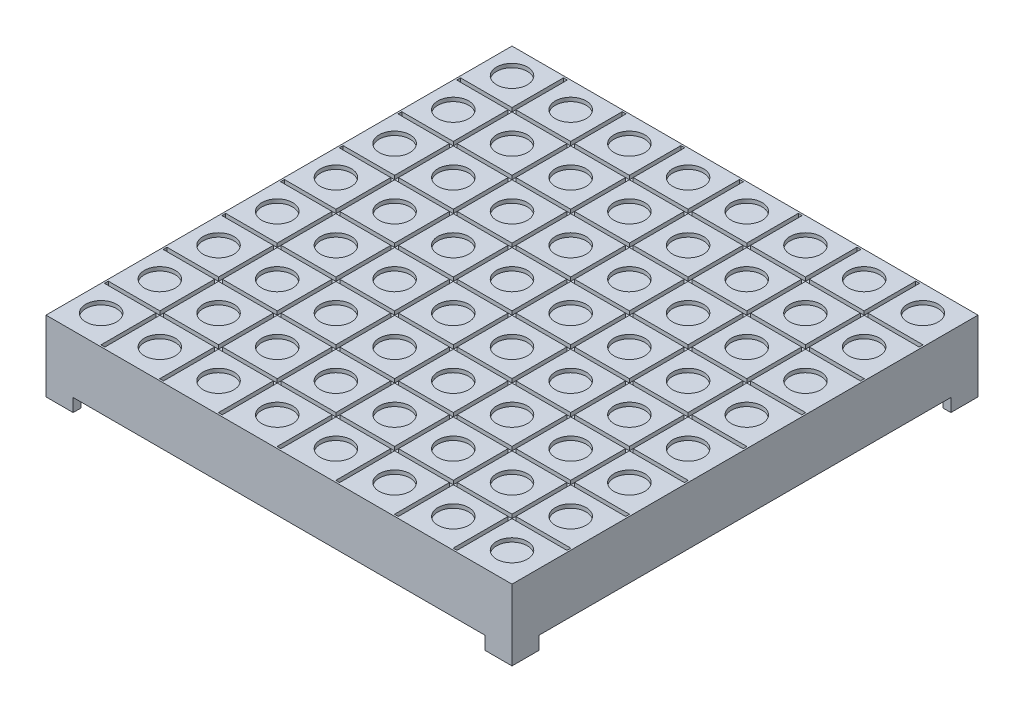
SolidWorks part; units mm, degrees
ref_plane "Спереди" through (0, 0, 0) normal (0, 0, 1) x (1, 0, 0)
ref_plane "Сверху" through (0, 0, 0) normal (0, 1, 0) x (1, 0, 0)
ref_plane "Справа" through (0, 0, 0) normal (1, 0, 0) x (0, 0, -1)
sketch "Эскиз2" plane through (0, 0, 0) normal (0, 1, 0) x (1, 0, 0)
  line L1 (-30.25, 30.25) -> (30.25, 30.25)
  line L2 (-30.25, 30.25) -> (-30.25, -30.25)
  line L3 (-30.25, -30.25) -> (30.25, -30.25)
  line L4 (30.25, 30.25) -> (30.25, -30.25)
  line L5 (-30.25, 30.25) -> (30.25, -30.25) construction
  line L6 (-30.25, -30.25) -> (30.25, 30.25) construction
  point P0 (0, 0)
extrude "Бобышка-Вытянуть1" add sketch "Эскиз2" along normal blind 7.5
sketch "Эскиз3" plane through (0, 7.5, 0) normal (0, 1, 0) x (1, 0, 0)
  line L0 (22.885, -30.025) -> (22.885, -22.885)
  line L1 (22.885, -30.025) -> (22.385, -30.025)
  line L2 (-23.335, -14.765) -> (-23.335, -7.645)
  line L3 (-22.835, -14.765) -> (-22.835, -7.645)
  line L4 (22.385, -30.025) -> (22.385, -22.885)
  line L5 (22.885, 30.025) -> (22.385, 30.025)
  line L6 (15.265, -30.025) -> (15.265, -22.885)
  line L7 (15.265, -30.025) -> (14.765, -30.025)
  line L8 (14.765, -30.025) -> (14.765, -22.885)
  line L9 (15.265, 30.025) -> (14.765, 30.025)
  line L10 (7.645, -30.025) -> (7.645, -22.885)
  line L11 (7.645, -30.025) -> (7.145, -30.025)
  line L12 (7.145, -30.025) -> (7.145, -22.885)
  line L13 (7.645, 30.025) -> (7.145, 30.025)
  line L14 (0.025, -30.025) -> (0.025, -22.885)
  line L15 (0.025, -30.025) -> (-0.475, -30.025)
  line L16 (-0.475, -30.025) -> (-0.475, -22.885)
  line L17 (0.025, 30.025) -> (-0.475, 30.025)
  line L18 (-7.595, -30.025) -> (-7.595, -22.885)
  line L19 (-7.595, -30.025) -> (-8.095, -30.025)
  line L20 (-8.095, -30.025) -> (-8.095, -22.885)
  line L21 (-7.595, 30.025) -> (-8.095, 30.025)
  line L22 (-15.215, -30.025) -> (-15.215, -22.885)
  line L23 (-15.215, -30.025) -> (-15.715, -30.025)
  line L24 (-15.715, -30.025) -> (-15.715, -22.885)
  line L25 (-15.215, 30.025) -> (-15.715, 30.025)
  line L26 (-22.835, -30.025) -> (-22.835, -22.885)
  line L27 (-22.835, -30.025) -> (-23.335, -30.025)
  line L28 (-23.335, -30.025) -> (-23.335, -22.885)
  line L29 (-22.835, 30.025) -> (-23.335, 30.025)
  line L30 (30.025, -22.885) -> (22.885, -22.885)
  line L31 (30.025, -22.885) -> (30.025, -22.385)
  line L32 (-15.715, -14.765) -> (-15.715, -7.645)
  line L33 (-15.215, -14.765) -> (-15.215, -7.645)
  line L34 (30.025, -22.385) -> (22.885, -22.385)
  line L35 (-30.025, -22.885) -> (-30.025, -22.385)
  line L36 (-30.025, -15.265) -> (-30.025, -14.765)
  line L37 (30.025, -14.765) -> (22.885, -14.765)
  line L38 (30.025, -15.265) -> (22.885, -15.265)
  line L39 (30.025, -15.265) -> (30.025, -14.765)
  line L40 (-30.025, -7.645) -> (-30.025, -7.145)
  line L41 (30.025, -7.145) -> (22.885, -7.145)
  line L42 (30.025, -7.645) -> (22.885, -7.645)
  line L43 (30.025, -7.645) -> (30.025, -7.145)
  line L44 (-30.025, -0.025) -> (-30.025, 0.475)
  line L45 (30.025, 0.475) -> (22.885, 0.475)
  line L46 (30.025, -0.025) -> (22.885, -0.025)
  line L47 (30.025, -0.025) -> (30.025, 0.475)
  line L48 (-30.025, 7.595) -> (-30.025, 8.095)
  line L49 (30.025, 8.095) -> (22.885, 8.095)
  line L50 (30.025, 7.595) -> (22.885, 7.595)
  line L51 (30.025, 7.595) -> (30.025, 8.095)
  line L52 (-30.025, 15.215) -> (-30.025, 15.715)
  line L53 (30.025, 15.715) -> (22.885, 15.715)
  line L54 (30.025, 15.215) -> (22.885, 15.215)
  line L55 (30.025, 15.215) -> (30.025, 15.715)
  line L56 (-30.025, 22.835) -> (-30.025, 23.335)
  line L57 (30.025, 23.335) -> (22.885, 23.335)
  line L58 (30.025, 22.835) -> (22.885, 22.835)
  line L59 (30.025, 22.835) -> (30.025, 23.335)
  line L60 (22.385, -22.385) -> (22.385, -15.265)
  line L61 (22.885, -22.385) -> (22.885, -15.265)
  line L62 (22.385, -22.885) -> (15.265, -22.885)
  line L63 (22.385, -22.385) -> (15.265, -22.385)
  line L64 (14.765, -22.885) -> (7.645, -22.885)
  line L65 (14.765, -22.385) -> (7.645, -22.385)
  line L66 (14.765, -22.385) -> (14.765, -15.265)
  line L67 (15.265, -22.385) -> (15.265, -15.265)
  line L68 (7.145, -22.885) -> (0.025, -22.885)
  line L69 (7.145, -22.385) -> (0.025, -22.385)
  line L70 (7.145, -22.385) -> (7.145, -15.265)
  line L71 (7.645, -22.385) -> (7.645, -15.265)
  line L72 (-0.475, -22.885) -> (-7.595, -22.885)
  line L73 (-0.475, -22.385) -> (-7.595, -22.385)
  line L74 (-0.475, -22.385) -> (-0.475, -15.265)
  line L75 (0.025, -22.385) -> (0.025, -15.265)
  line L76 (-8.095, -22.885) -> (-15.215, -22.885)
  line L77 (-8.095, -22.385) -> (-15.215, -22.385)
  line L78 (-8.095, -22.385) -> (-8.095, -15.265)
  line L79 (-7.595, -22.385) -> (-7.595, -15.265)
  line L80 (-15.715, -22.885) -> (-22.835, -22.885)
  line L81 (-15.715, -22.385) -> (-22.835, -22.385)
  line L82 (-15.715, -22.385) -> (-15.715, -15.265)
  line L83 (-15.215, -22.385) -> (-15.215, -15.265)
  line L84 (-23.335, -22.885) -> (-30.025, -22.885)
  line L85 (-23.335, -22.385) -> (-30.025, -22.385)
  line L86 (-23.335, -22.385) -> (-23.335, -15.265)
  line L87 (-22.835, -22.385) -> (-22.835, -15.265)
  line L88 (-15.715, -15.265) -> (-22.835, -15.265)
  line L89 (-15.715, -14.765) -> (-22.835, -14.765)
  line L90 (-23.335, -15.265) -> (-30.025, -15.265)
  line L91 (-23.335, -14.765) -> (-30.025, -14.765)
  line L92 (-8.095, -15.265) -> (-15.215, -15.265)
  line L93 (-8.095, -14.765) -> (-15.215, -14.765)
  line L94 (-7.595, -14.765) -> (-7.595, -7.645)
  line L95 (-8.095, -14.765) -> (-8.095, -7.645)
  line L96 (-0.475, -15.265) -> (-7.595, -15.265)
  line L97 (-0.475, -14.765) -> (-7.595, -14.765)
  line L98 (0.025, -14.765) -> (0.025, -7.645)
  line L99 (-0.475, -14.765) -> (-0.475, -7.645)
  line L100 (7.145, -15.265) -> (0.025, -15.265)
  line L101 (7.145, -14.765) -> (0.025, -14.765)
  line L102 (7.645, -14.765) -> (7.645, -7.645)
  line L103 (7.145, -14.765) -> (7.145, -7.645)
  line L104 (14.765, -15.265) -> (7.645, -15.265)
  line L105 (14.765, -14.765) -> (7.645, -14.765)
  line L106 (15.265, -14.765) -> (15.265, -7.645)
  line L107 (14.765, -14.765) -> (14.765, -7.645)
  line L108 (22.385, -15.265) -> (15.265, -15.265)
  line L109 (22.385, -14.765) -> (15.265, -14.765)
  line L110 (22.885, -14.765) -> (22.885, -7.645)
  line L111 (22.385, -14.765) -> (22.385, -7.645)
  line L112 (22.385, -7.645) -> (15.265, -7.645)
  line L113 (22.385, -7.145) -> (15.265, -7.145)
  line L114 (22.885, -7.145) -> (22.885, -0.025)
  line L115 (22.385, -7.145) -> (22.385, -0.025)
  line L116 (14.765, -7.145) -> (14.765, -0.025)
  line L117 (15.265, -7.145) -> (15.265, -0.025)
  line L118 (14.765, -7.645) -> (7.645, -7.645)
  line L119 (14.765, -7.145) -> (7.645, -7.145)
  line L120 (7.145, -7.145) -> (7.145, -0.025)
  line L121 (7.645, -7.145) -> (7.645, -0.025)
  line L122 (7.145, -7.645) -> (0.025, -7.645)
  line L123 (7.145, -7.145) -> (0.025, -7.145)
  line L124 (-0.475, -7.145) -> (-0.475, -0.025)
  line L125 (0.025, -7.145) -> (0.025, -0.025)
  line L126 (-0.475, -7.645) -> (-7.595, -7.645)
  line L127 (-0.475, -7.145) -> (-7.595, -7.145)
  line L128 (-8.095, -7.145) -> (-8.095, -0.025)
  line L129 (-7.595, -7.145) -> (-7.595, -0.025)
  line L130 (-8.095, -7.645) -> (-15.215, -7.645)
  line L131 (-8.095, -7.145) -> (-15.215, -7.145)
  line L132 (-15.715, -7.145) -> (-15.715, -0.025)
  line L133 (-15.215, -7.145) -> (-15.215, -0.025)
  line L134 (-15.715, -7.645) -> (-22.835, -7.645)
  line L135 (-15.715, -7.145) -> (-22.835, -7.145)
  line L136 (-23.335, -7.145) -> (-23.335, -0.025)
  line L137 (-22.835, -7.145) -> (-22.835, -0.025)
  line L138 (-23.335, -7.645) -> (-30.025, -7.645)
  line L139 (-23.335, -7.145) -> (-30.025, -7.145)
  line L140 (-23.335, 0.475) -> (-23.335, 7.595)
  line L141 (-22.835, 0.475) -> (-22.835, 7.595)
  line L142 (-23.335, -0.025) -> (-30.025, -0.025)
  line L143 (-23.335, 0.475) -> (-30.025, 0.475)
  line L144 (-15.715, 0.475) -> (-15.715, 7.595)
  line L145 (-15.215, 0.475) -> (-15.215, 7.595)
  line L146 (-15.715, -0.025) -> (-22.835, -0.025)
  line L147 (-15.715, 0.475) -> (-22.835, 0.475)
  line L148 (-8.095, 0.475) -> (-8.095, 7.595)
  line L149 (-7.595, 0.475) -> (-7.595, 7.595)
  line L150 (-8.095, -0.025) -> (-15.215, -0.025)
  line L151 (-8.095, 0.475) -> (-15.215, 0.475)
  line L152 (-0.475, 0.475) -> (-0.475, 7.595)
  line L153 (0.025, 0.475) -> (0.025, 7.595)
  line L154 (-0.475, -0.025) -> (-7.595, -0.025)
  line L155 (-0.475, 0.475) -> (-7.595, 0.475)
  line L156 (7.145, 0.475) -> (7.145, 7.595)
  line L157 (7.645, 0.475) -> (7.645, 7.595)
  line L158 (7.145, -0.025) -> (0.025, -0.025)
  line L159 (7.145, 0.475) -> (0.025, 0.475)
  line L160 (14.765, 0.475) -> (14.765, 7.595)
  line L161 (15.265, 0.475) -> (15.265, 7.595)
  line L162 (14.765, -0.025) -> (7.645, -0.025)
  line L163 (14.765, 0.475) -> (7.645, 0.475)
  line L164 (22.385, 0.475) -> (22.385, 7.595)
  line L165 (22.885, 0.475) -> (22.885, 7.595)
  line L166 (22.385, -0.025) -> (15.265, -0.025)
  line L167 (22.385, 0.475) -> (15.265, 0.475)
  line L168 (22.385, 8.095) -> (22.385, 15.215)
  line L169 (22.885, 8.095) -> (22.885, 15.215)
  line L170 (22.385, 7.595) -> (15.265, 7.595)
  line L171 (22.385, 8.095) -> (15.265, 8.095)
  line L172 (14.765, 7.595) -> (7.645, 7.595)
  line L173 (14.765, 8.095) -> (7.645, 8.095)
  line L174 (15.265, 8.095) -> (15.265, 15.215)
  line L175 (14.765, 8.095) -> (14.765, 15.215)
  line L176 (7.145, 7.595) -> (0.025, 7.595)
  line L177 (7.145, 8.095) -> (0.025, 8.095)
  line L178 (7.145, 8.095) -> (7.145, 15.215)
  line L179 (7.645, 8.095) -> (7.645, 15.215)
  line L180 (-0.475, 7.595) -> (-7.595, 7.595)
  line L181 (-0.475, 8.095) -> (-7.595, 8.095)
  line L182 (-0.475, 8.095) -> (-0.475, 15.215)
  line L183 (0.025, 8.095) -> (0.025, 15.215)
  line L184 (-8.095, 7.595) -> (-15.215, 7.595)
  line L185 (-8.095, 8.095) -> (-15.215, 8.095)
  line L186 (-8.095, 8.095) -> (-8.095, 15.215)
  line L187 (-7.595, 8.095) -> (-7.595, 15.215)
  line L188 (-15.715, 7.595) -> (-22.835, 7.595)
  line L189 (-15.715, 8.095) -> (-22.835, 8.095)
  line L190 (-15.715, 8.095) -> (-15.715, 15.215)
  line L191 (-15.215, 8.095) -> (-15.215, 15.215)
  line L192 (-23.335, 7.595) -> (-30.025, 7.595)
  line L193 (-23.335, 8.095) -> (-30.025, 8.095)
  line L194 (-23.335, 8.095) -> (-23.335, 15.215)
  line L195 (-22.835, 8.095) -> (-22.835, 15.215)
  line L196 (22.385, 15.215) -> (15.265, 15.215)
  line L197 (22.385, 15.715) -> (15.265, 15.715)
  line L198 (22.885, 15.715) -> (22.885, 22.835)
  line L199 (22.385, 15.715) -> (22.385, 22.835)
  line L200 (14.765, 15.215) -> (7.645, 15.215)
  line L201 (14.765, 15.715) -> (7.645, 15.715)
  line L202 (15.265, 15.715) -> (15.265, 22.835)
  line L203 (14.765, 15.715) -> (14.765, 22.835)
  line L204 (7.145, 15.215) -> (0.025, 15.215)
  line L205 (7.145, 15.715) -> (0.025, 15.715)
  line L206 (7.145, 15.715) -> (7.145, 22.835)
  line L207 (7.645, 15.715) -> (7.645, 22.835)
  line L208 (-0.475, 15.215) -> (-7.595, 15.215)
  line L209 (-0.475, 15.715) -> (-7.595, 15.715)
  line L210 (-0.475, 15.715) -> (-0.475, 22.835)
  line L211 (0.025, 15.715) -> (0.025, 22.835)
  line L212 (-8.095, 15.215) -> (-15.215, 15.215)
  line L213 (-8.095, 15.715) -> (-15.215, 15.715)
  line L214 (-8.095, 15.715) -> (-8.095, 22.835)
  line L215 (-7.595, 15.715) -> (-7.595, 22.835)
  line L216 (-15.715, 15.215) -> (-22.835, 15.215)
  line L217 (-15.715, 15.715) -> (-22.835, 15.715)
  line L218 (-15.215, 15.715) -> (-15.215, 22.835)
  line L219 (-15.715, 15.715) -> (-15.715, 22.835)
  line L220 (-23.335, 15.215) -> (-30.025, 15.215)
  line L221 (-23.335, 15.715) -> (-30.025, 15.715)
  line L222 (-22.835, 15.715) -> (-22.835, 22.835)
  line L223 (-23.335, 15.715) -> (-23.335, 22.835)
  line L224 (-23.335, 23.335) -> (-23.335, 30.025)
  line L225 (-22.835, 23.335) -> (-22.835, 30.025)
  line L226 (-23.335, 22.835) -> (-30.025, 22.835)
  line L227 (-23.335, 23.335) -> (-30.025, 23.335)
  line L228 (-15.715, 23.335) -> (-15.715, 30.025)
  line L229 (-15.215, 23.335) -> (-15.215, 30.025)
  line L230 (-15.715, 22.835) -> (-22.835, 22.835)
  line L231 (-15.715, 23.335) -> (-22.835, 23.335)
  line L232 (-8.095, 23.335) -> (-8.095, 30.025)
  line L233 (-7.595, 23.335) -> (-7.595, 30.025)
  line L234 (-8.095, 22.835) -> (-15.215, 22.835)
  line L235 (-8.095, 23.335) -> (-15.215, 23.335)
  line L236 (-0.475, 23.335) -> (-0.475, 30.025)
  line L237 (0.025, 23.335) -> (0.025, 30.025)
  line L238 (-0.475, 22.835) -> (-7.595, 22.835)
  line L239 (-0.475, 23.335) -> (-7.595, 23.335)
  line L240 (7.145, 23.335) -> (7.145, 30.025)
  line L241 (7.645, 23.335) -> (7.645, 30.025)
  line L242 (7.145, 23.335) -> (0.025, 23.335)
  line L243 (7.145, 22.835) -> (0.025, 22.835)
  line L244 (14.765, 23.335) -> (14.765, 30.025)
  line L245 (15.265, 23.335) -> (15.265, 30.025)
  line L246 (14.765, 22.835) -> (7.645, 22.835)
  line L247 (14.765, 23.335) -> (7.645, 23.335)
  line L248 (22.385, 23.335) -> (22.385, 30.025)
  line L249 (22.885, 23.335) -> (22.885, 30.025)
  line L250 (22.385, 23.335) -> (15.265, 23.335)
  line L251 (22.385, 22.835) -> (15.265, 22.835)
  circle A0 centre (26.445, -26.445) radius 2
  circle A1 centre (18.825, -26.445) radius 2
  circle A2 centre (11.205, -26.445) radius 2
  circle A3 centre (3.585, -26.445) radius 2
  circle A4 centre (-4.035, -26.445) radius 2
  circle A5 centre (-11.655, -26.445) radius 2
  circle A6 centre (-19.275, -26.445) radius 2
  circle A7 centre (-26.895, -26.445) radius 2
  circle A8 centre (18.825, -18.825) radius 2
  circle A9 centre (11.205, -18.825) radius 2
  circle A10 centre (3.585, -18.825) radius 2
  circle A11 centre (-4.035, -18.825) radius 2
  circle A12 centre (-11.655, -18.825) radius 2
  circle A13 centre (-19.275, -18.825) radius 2
  circle A14 centre (-26.895, -18.825) radius 2
  circle A15 centre (18.825, -11.205) radius 2
  circle A16 centre (11.205, -11.205) radius 2
  circle A17 centre (3.585, -11.205) radius 2
  circle A18 centre (-4.035, -11.205) radius 2
  circle A19 centre (-11.655, -11.205) radius 2
  circle A20 centre (-19.275, -11.205) radius 2
  circle A21 centre (-26.895, -11.205) radius 2
  circle A22 centre (18.825, -3.585) radius 2
  circle A23 centre (11.205, -3.585) radius 2
  circle A24 centre (3.585, -3.585) radius 2
  circle A25 centre (-4.035, -3.585) radius 2
  circle A26 centre (-11.655, -3.585) radius 2
  circle A27 centre (-19.275, -3.585) radius 2
  circle A28 centre (-26.895, -3.585) radius 2
  circle A29 centre (18.825, 4.035) radius 2
  circle A30 centre (11.205, 4.035) radius 2
  circle A31 centre (3.585, 4.035) radius 2
  circle A32 centre (-4.035, 4.035) radius 2
  circle A33 centre (-11.655, 4.035) radius 2
  circle A34 centre (-19.275, 4.035) radius 2
  circle A35 centre (-26.895, 4.035) radius 2
  circle A36 centre (18.825, 11.655) radius 2
  circle A37 centre (11.205, 11.655) radius 2
  circle A38 centre (3.585, 11.655) radius 2
  circle A39 centre (-4.035, 11.655) radius 2
  circle A40 centre (-11.655, 11.655) radius 2
  circle A41 centre (-19.275, 11.655) radius 2
  circle A42 centre (-26.895, 11.655) radius 2
  circle A43 centre (18.825, 19.275) radius 2
  circle A44 centre (11.205, 19.275) radius 2
  circle A45 centre (3.585, 19.275) radius 2
  circle A46 centre (-4.035, 19.275) radius 2
  circle A47 centre (-11.655, 19.275) radius 2
  circle A48 centre (-19.275, 19.275) radius 2
  circle A49 centre (-26.895, 19.275) radius 2
  circle A50 centre (18.825, 26.895) radius 2
  circle A51 centre (11.205, 26.895) radius 2
  circle A52 centre (3.585, 26.895) radius 2
  circle A53 centre (-4.035, 26.895) radius 2
  circle A54 centre (-11.655, 26.895) radius 2
  circle A55 centre (-19.275, 26.895) radius 2
  circle A56 centre (-26.895, 26.895) radius 2
  circle A57 centre (26.445, -18.825) radius 2
  circle A58 centre (26.445, -11.205) radius 2
  circle A59 centre (26.445, -3.585) radius 2
  circle A60 centre (26.445, 4.035) radius 2
  circle A61 centre (26.445, 11.655) radius 2
  circle A62 centre (26.445, 19.275) radius 2
  circle A63 centre (26.445, 26.895) radius 2
  dimension "D1" = 8
  dimension "D2" = 8
sketch "Эскиз4" plane through (0, 0, 0) normal (0, -1, 0) x (1, 0, 0)
  line L1 (29.25, 29.25) -> (-29.25, 29.25)
  line L2 (29.25, 29.25) -> (29.25, -29.25)
  line L3 (29.25, -29.25) -> (-29.25, -29.25)
  line L4 (-29.25, 29.25) -> (-29.25, -29.25)
  line L5 (29.25, 29.25) -> (-29.25, -29.25) construction
  line L6 (29.25, -29.25) -> (-29.25, 29.25) construction
  point P0 (0, 0)
extrude "Вырез-Вытянуть2" cut sketch "Эскиз4" against normal blind 1
sketch "Эскиз5" plane through (0, 0, 0) normal (0, -1, 0) x (1, 0, 0)
  line L2 (26.725, 30.25) -> (30.25, 30.25)
  line L3 (26.725, 29.25) -> (26.725, 30.25)
  line L4 (29.25, 29.25) -> (26.725, 29.25)
  line L5 (29.25, 26.725) -> (29.25, 29.25)
  line L6 (30.25, 26.725) -> (29.25, 26.725)
  line L7 (30.25, 30.25) -> (30.25, 26.725)
  line L8 (-26.725, -30.25) -> (-30.25, -30.25)
  line L9 (-26.725, -29.25) -> (-26.725, -30.25)
  line L10 (-29.25, -29.25) -> (-26.725, -29.25)
  line L11 (-29.25, -26.725) -> (-29.25, -29.25)
  line L12 (-30.25, -26.725) -> (-29.25, -26.725)
  line L13 (-30.25, -30.25) -> (-30.25, -26.725)
  line L14 (-30.25, 30.25) -> (-30.25, 26.725)
  line L15 (-30.25, 26.725) -> (-29.25, 26.725)
  line L16 (-29.25, 26.725) -> (-29.25, 29.25)
  line L17 (-29.25, 29.25) -> (-26.725, 29.25)
  line L18 (-26.725, 29.25) -> (-26.725, 30.25)
  line L19 (30.25, -30.25) -> (30.25, -26.725)
  line L20 (30.25, -26.725) -> (29.25, -26.725)
  line L21 (29.25, -26.725) -> (29.25, -29.25)
  line L22 (29.25, -29.25) -> (26.725, -29.25)
  line L23 (26.725, -29.25) -> (26.725, -30.25)
  line L24 (26.725, -30.25) -> (30.25, -30.25)
  line L25 (-26.725, 30.25) -> (-30.25, 30.25)
extrude "Бобышка-Вытянуть2" add sketch "Эскиз5" along normal blind 1.7
extrude "Вырез-Вытянуть4" cut sketch "Эскиз3" against normal blind 0.5
sketch "Эскиз8" plane through (0, 1, 0) normal (0, -1, 0) x (1, 0, 0)
  circle A0 centre (19.05, -22.86) radius 0.5
  circle A1 centre (16.51, -22.86) radius 0.5
  circle A2 centre (13.97, -22.86) radius 0.5
  circle A3 centre (11.43, -22.86) radius 0.5
  circle A4 centre (8.89, -22.86) radius 0.5
  circle A5 centre (6.35, -22.86) radius 0.5
  circle A6 centre (3.81, -22.86) radius 0.5
  circle A7 centre (1.27, -22.86) radius 0.5
  circle A8 centre (-1.27, -22.86) radius 0.5
  circle A9 centre (-3.81, -22.86) radius 0.5
  circle A10 centre (-6.35, -22.86) radius 0.5
  circle A11 centre (-8.89, -22.86) radius 0.5
  circle A12 centre (-11.43, -22.86) radius 0.5
  circle A13 centre (-13.97, -22.86) radius 0.5
  circle A14 centre (-16.51, -22.86) radius 0.5
  circle A15 centre (-19.05, 22.86) radius 0.5
  circle A16 centre (-16.51, 22.86) radius 0.5
  circle A17 centre (-13.97, 22.86) radius 0.5
  circle A18 centre (-11.43, 22.86) radius 0.5
  circle A19 centre (-8.89, 22.86) radius 0.5
  circle A20 centre (-6.35, 22.86) radius 0.5
  circle A21 centre (-3.81, 22.86) radius 0.5
  circle A22 centre (-1.27, 22.86) radius 0.5
  circle A23 centre (1.27, 22.86) radius 0.5
  circle A24 centre (3.81, 22.86) radius 0.5
  circle A25 centre (6.35, 22.86) radius 0.5
  circle A26 centre (8.89, 22.86) radius 0.5
  circle A27 centre (11.43, 22.86) radius 0.5
  circle A28 centre (13.97, 22.86) radius 0.5
  circle A29 centre (16.51, 22.86) radius 0.5
  circle A30 centre (-19.05, -22.86) radius 0.5
  circle A31 centre (19.05, 22.86) radius 0.5
  dimension "D1" = 16
extrude "Бобышка-Вытянуть3" add sketch "Эскиз8" along normal blind 3
